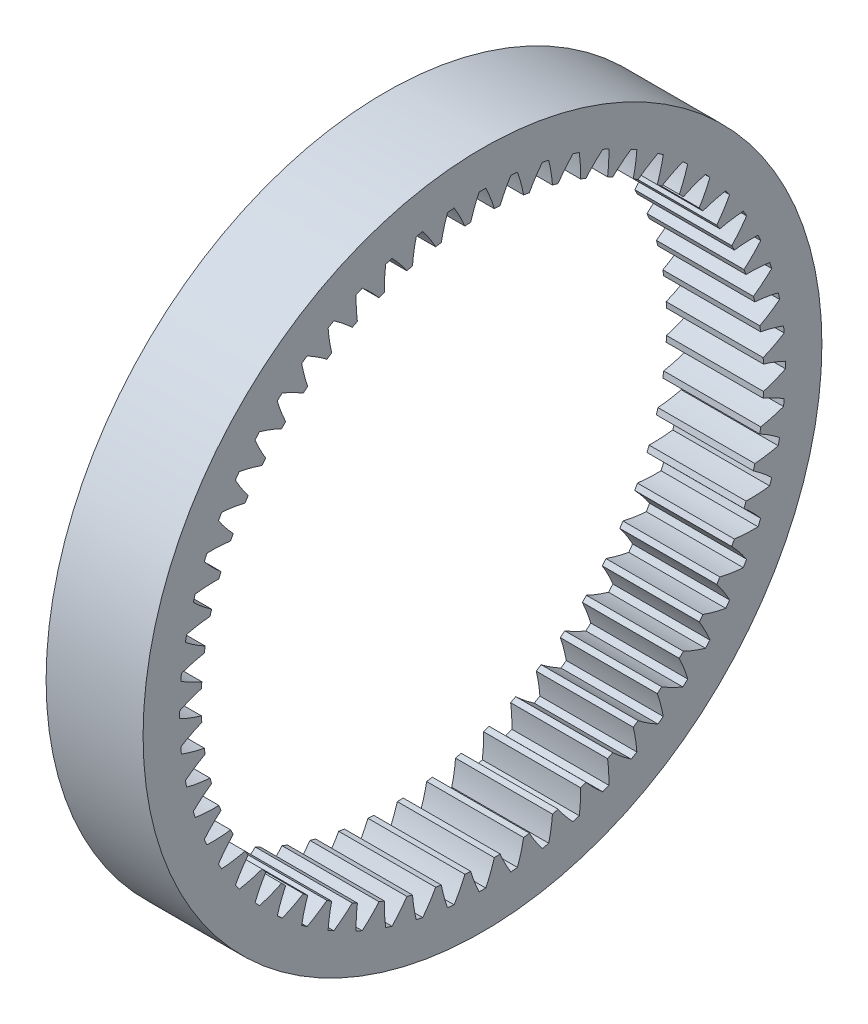
SolidWorks part; units mm, degrees
ref_plane "Plane1" through (0, 0, 0) normal (0, 0, 1) x (1, 0, 0)
ref_plane "Plane2" through (0, 0, 0) normal (0, 1, 0) x (1, 0, 0)
ref_plane "Plane3" through (0, 0, 0) normal (1, 0, 0) x (0, 0, -1)
sketch "HoldingSke" plane through (0, 0, 0) normal (0, 1, 0) x (1, 0, 0)
  line L0 (0, 0) -> (0.5, -0.866)
  line L1 (-15, 0) -> (100, 0) construction
  line L2 (0, 0) -> (-2.1039, 2.3779)
  line L3 (0, 0) -> (-11.863, 4.5341)
  line L4 (0, 0) -> (4.318, 7.479)
  line L5 (0, 0) -> (-23.7986, -8.8762)
  line L6 (0, 0) -> (-10.5278, -7.1032)
  line L7 (-2.1039, 2.3779) -> (3.3635, 27.1825)
  line L8 (-76.2, 3.3779) -> (-54.61, 3.3779)
  line L9 (-71.009, 38.7566) -> (-53.1078, 45.2721)
  line L10 (-76.2, 71.12) -> (104.1128, 71.12)
  line L11 (0, 0) -> (-10, 0)
  line L12 (-76.2, 101.6) -> (-76.162, 101.6)
  line L13 (24.9733, 27.94) -> (52.9518, 28.4284)
  line L14 (24.9733, 27.94) -> (24.9743, 27.94)
  line L15 (24.9733, 27.94) -> (100.4006, 29.5858)
  circle A0 centre (0, 0) radius 35
  circle A1 centre (0, 0) radius 12.7
  circle A2 centre (0, 0) radius 12.7
  dimension "MHD" = 25.4
  dimension "Hub_dia" = 25.4
  dimension "Diameter" = 70
  dimension "Num_teeth" = 60
  dimension "Pitch" = 1
  dimension "Overall_len" = 25.4
  dimension "Show_teeth" = 60
  dimension "Thickness" = 12.7
  dimension "OAL" = 25.4001
  dimension "T_dim" = 21.59
  dimension "Ap" = 20
  dimension "H" = 19.05
  dimension "Pitch_radius" = 180.3128
  dimension "Width" = 10
  dimension "Backlash" = 0.038
  dimension "Addendum_fac" = 1
  dimension "Dedendum_fac" = 1.25
  dimension "Clearance_fac" = 0.25
  dimension "Dedendum_add" = 0.001
  dimension "Module" = 1
sketch "BasProSke" plane through (0, 0, 0) normal (0, 1, 0) x (1, 0, 0)
  line L0 (-10, 0) -> (60, 0) construction
  line L1 (0, 29) -> (0, 35)
  line L2 (0, 29) -> (10, 29)
  line L3 (10, 29) -> (10, 35)
  line L4 (10, 35) -> (0, 35)
  dimension "Diameter" = 70
  dimension "Thickness" = 10
  dimension "Inside_diameter" = 58
revolve "Base-Revolve" add sketch "BasProSke" angle 360 about L0
sketch "TooCutSke" plane through (0, 0, 0) normal (1, 0, 0) x (0, 0, -1)
  line L3 (0.8803, 29.9871) -> (0.8803, 53.6633) construction
  line L4 (0, 0) -> (0, 59.563) construction
  line L5 (0, 0) -> (-3.576, 68.2339) construction
  line L6 (-13.1633, 24.7167) -> (36.4631, 27.3175) construction
  circle A0 centre (0, 0) radius 30 construction
  circle A1 centre (0, 0) radius 31.251 construction
  circle A2 centre (0, 0) radius 25.3717 construction
  circle A3 centre (0, 0) radius 28.9746 construction
  arc A4 (1.2274, 28.9486) -> (0.3395, 31.2492) centre (-13.1633, 24.7167) ccw
  arc A5 (1.2274, 28.9486) -> (-1.2274, 28.9486) centre (0, 0) ccw
  arc A6 (0.3395, 31.2492) -> (-0.3395, 31.2492) centre (0, 0) ccw
  arc A7 (-0.3395, 31.2492) -> (-1.2274, 28.9486) centre (13.1633, 24.7167) ccw
  dimension "Pitch_dia" = 60
  dimension "Base_dia" = 50.7434
  dimension "Root_dia" = 62.502
  dimension "Overcut_dia" = 57.9492
  dimension "Flank_rad" = 15
  dimension "Half_ang" = 3
  dimension "Half_CT" = 0.8803
extrude "ToothCut" cut sketch "TooCutSke" along normal through all
fillet "Breaks" [suppressed] radius 0.1
fillet "RootFillets" [suppressed] radius 0.251
pattern_circular "TeethCuts" count 60 every 6 about axis through (-10, 0, 0) along (1, 0, 0) of "RootFillets", "Breaks", "ToothCut"
equation "' \"Module@HoldingSke\" = 6.35"
equation "' \"Num_teeth@HoldingSke\" = 24"
equation "' \"Ap@HoldingSke\" =  14.5"
equation "' \"Ap@HoldingSke\" = 14.5"
equation "' \"Width@HoldingSke\" = 12"
equation "' \"Diameter@HoldingSke\" = 8 * 25.4"
equation "' \"Show_teeth@HoldingSke\" = 100"
equation "' \"Backlash@HoldingSke\" = 0.009 * 25.4"
equation "' \"Addendum_fac@HoldingSke\" = 1.0"
equation "' \"Dedendum_fac@HoldingSke\" = 1.25"
equation "' \"Dedendum_add@HoldingSke\" = 0.00005 * 25.4"
equation "' \"Clearance_fac@HoldingSke\" = 0.25"
equation "\"Pitch@HoldingSke\" = 1 / \"Module@HoldingSke\" "
equation "\"Overcut_dia@TooCutSke\" = (\"Num_teeth@HoldingSke\" - 2 * \"Addendum_fac@HoldingSke\") / \"Pitch@HoldingSke\" - 0.002 * 25.4"
equation "\"Pitch_dia@TooCutSke\" = \"Num_teeth@HoldingSke\" / \"Pitch@HoldingSke\""
equation "\"Base_dia@TooCutSke\" = \"Num_teeth@HoldingSke\" / \"Pitch@HoldingSke\" * cos((\"Ap@HoldingSke\"  * 3.14159265 / 180)) * 0.90"
equation "\"Root_dia@TooCutSke\" = \"Num_teeth@HoldingSke\"  / \"Pitch@HoldingSke\" + 2 *  \"Dedendum_fac@HoldingSke\"/ \"Pitch@HoldingSke\" + \"Dedendum_add@HoldingSke\" * 2"
equation "\"Half_ang@TooCutSke\" = 180 / \"Num_teeth@HoldingSke\""
equation "\"Half_CT@TooCutSke\" = \"Num_teeth@HoldingSke\" / \"Pitch@HoldingSke\" * sin((3.14159265 / 2 / \"Num_teeth@HoldingSke\")) / 2 + 10 * \"Backlash@HoldingSke\" / 4"
equation "\"Flank_rad@TooCutSke\" = \"Num_teeth@HoldingSke\" / \"Pitch@HoldingSke\" / 4"
equation "\"Radius@RootFillets\"= \"Clearance_fac@HoldingSke\" / \"Pitch@HoldingSke\" + \"Dedendum_add@HoldingSke\""
equation "\"Break_rad@Breaks\" = 0.02 / \"Pitch@HoldingSke\" * 5"
equation "\"Num_teeth@TeethCuts\" = int( \"Show_teeth@HoldingSke\" ) + 1"
equation "\"Num_teeth@TeethCuts\" = ((sgn( \"Num_teeth@TeethCuts\" - \"Num_teeth@HoldingSke\" )-1)*( \"Num_teeth@TeethCuts\" - \"Num_teeth@HoldingSke\" ))/-2+ \"Num_teeth@HoldingSke\""
equation "\"Num_teeth@TeethCuts\" = ((sgn( \"Num_teeth@TeethCuts\" - 2.0)+1)*( \"Num_teeth@TeethCuts\" - 2.0))/2 +2.0"
equation "\"Angle@TeethCuts\" = 360.0 / \"Num_teeth@HoldingSke\""
equation "\"Diameter@BasProSke\" = \"Num_teeth@HoldingSke\"  / \"Pitch@HoldingSke\" + 2 *  \"Dedendum_fac@HoldingSke\"/ \"Pitch@HoldingSke\" + \"Dedendum_add@HoldingSke\" * 2 + 0.002 * 25.4"
equation "\"Diameter@BasProSke\" = ((sgn( \"Diameter@BasProSke\"  - \"Diameter@HoldingSke\" )+1)*( \"Diameter@BasProSke\"  - \"Diameter@HoldingSke\" ))/2 + \"Diameter@HoldingSke\""
equation "\"Inside_diameter@BasProSke\" =  (\"Num_teeth@HoldingSke\" - 2 * \"Addendum_fac@HoldingSke\") / \"Pitch@HoldingSke\" "
equation "\"Thickness@BasProSke\"  = \"Width@HoldingSke\""
